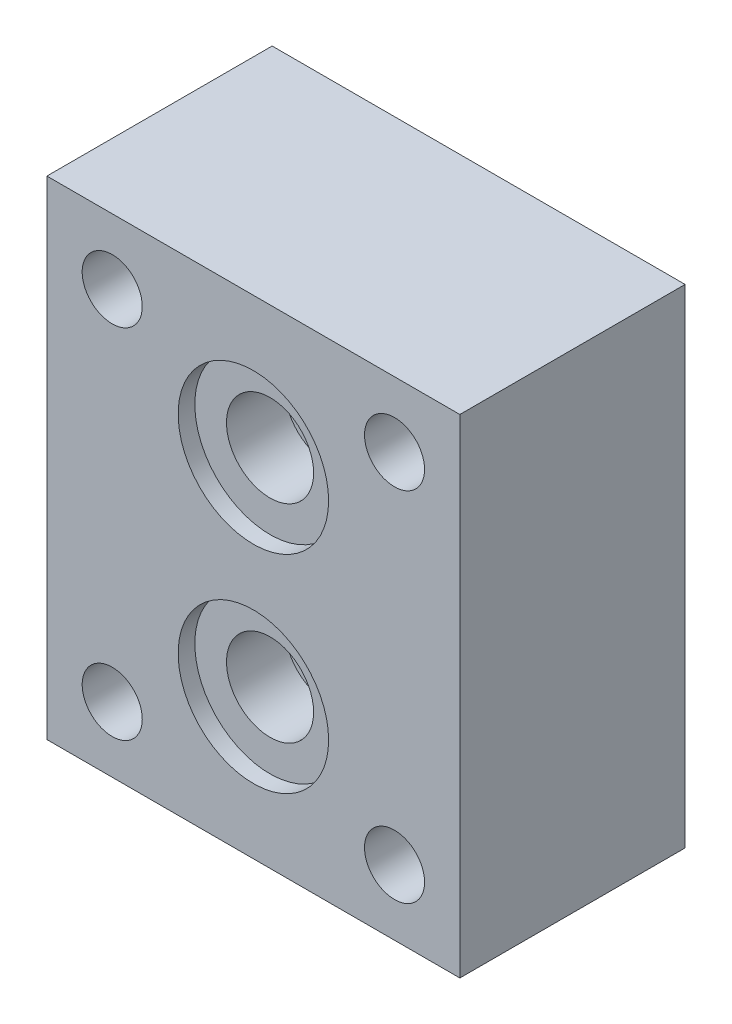
SolidWorks part; units mm, degrees
ref_plane "Front Plane" through (0, 0, 0) normal (1, 0, 0) x (0, 1, 0)
ref_plane "Top Plane" through (0, 0, 0) normal (0, 0, 1) x (0, 1, 0)
ref_plane "Right Plane" through (0, 0, 0) normal (0, 1, 0) x (-1, 0, 0)
sketch "Sketch1" plane through (0, 0, 0) normal (0, 0, 1) x (0, 1, 0)
  line L1 (-41.275, -34.925) -> (41.275, -34.925)
  line L2 (-41.275, -34.925) -> (-41.275, 34.925)
  line L3 (-41.275, 34.925) -> (41.275, 34.925)
  line L4 (41.275, -34.925) -> (41.275, 34.925)
  line L5 (-41.275, -34.925) -> (41.275, 34.925) construction
  line L6 (-41.275, 34.925) -> (41.275, -34.925) construction
  point P0 (0, 0)
extrude "Boss-Extrude1" add sketch "Sketch1" along normal mid plane 38.1
sketch "Sketch2" plane through (0, 0, 0) normal (0, 0, 1) x (0, 1, 0)
  circle A0 centre (-30.226, -23.876) radius 5.08
extrude "Cut-Extrude2" cut sketch "Sketch2" against normal up to next from offset 19.05
sketch "Sketch3" plane through (0, 0, 0) normal (0, 0, 1) x (0, 1, 0)
  circle A0 centre (30.226, -23.876) radius 5.08
  circle A1 centre (-30.226, 23.876) radius 5.08
  circle A2 centre (30.226, 23.876) radius 5.08
extrude "Cut-Extrude4" cut sketch "Sketch3" against normal up to next from offset 19.05
sketch "Sketch4" plane through (0, 0, 0) normal (0, 0, 1) x (0, 1, 0)
  circle A0 centre (-17.526, 0) radius 7.366
extrude "Cut-Extrude6" cut sketch "Sketch4" against normal blind 12.7 from offset 19.05
sketch "Sketch5" plane through (0, 0, 0) normal (0, 0, 1) x (0, 1, 0)
  circle A0 centre (-17.526, 0) radius 12.7254
extrude "Cut-Extrude8" cut sketch "Sketch5" against normal blind 2.8194 from offset 19.05
sketch "Sketch6" plane through (0, 0, 0) normal (0, 0, 1) x (0, 1, 0)
  circle A0 centre (17.526, 0) radius 7.366
extrude "Cut-Extrude10" cut sketch "Sketch6" against normal blind 12.7 from offset 19.05
sketch "Sketch7" plane through (0, 0, 0) normal (0, 0, 1) x (0, 1, 0)
  circle A0 centre (17.526, 0) radius 12.7254
extrude "Cut-Extrude12" cut sketch "Sketch7" against normal blind 2.8194 from offset 19.05
